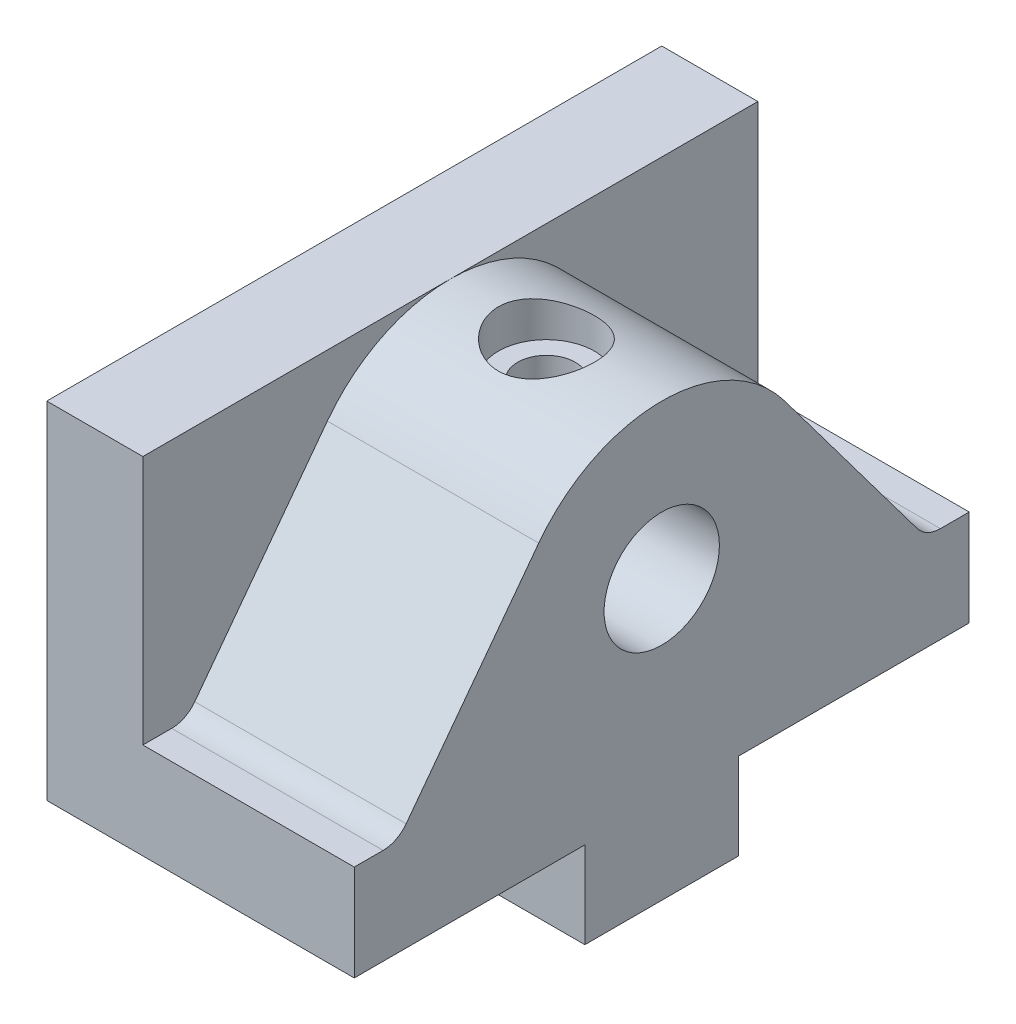
SolidWorks part; units mm, degrees
material "Gray Cast Iron"
ref_plane "Front Plane" through (0, 0, 0) normal (0, 0, 1) x (1, 0, 0)
ref_plane "Top Plane" through (0, 0, 0) normal (0, 1, 0) x (1, 0, 0)
ref_plane "Right Plane" through (0, 0, 0) normal (1, 0, 0) x (0, 0, -1)
sketch "Sketch1" plane through (0, 0, 0) normal (1, 0, 0) x (0, 0, -1)
  line L0 (8, -18) -> (32, -18)
  line L1 (-32, 18) -> (32, 18)
  line L2 (-32, 18) -> (-32, -18)
  line L3 (-32, -18) -> (-8, -18)
  line L4 (32, 18) -> (32, -18)
  line L5 (0, -18) -> (0, 18) construction
  line L6 (-32, 0) -> (32, 0) construction
  line L7 (-8, -27) -> (8, -27)
  line L8 (-8, -27) -> (-8, -18)
  line L10 (8, -27) -> (8, -18)
  line L11 (0, -18) -> (0, -27) construction
  line L12 (-8, -22.5) -> (8, -22.5) construction
  point P0 (0, 0)
  point P4 (0, -22.5)
  dimension "D1" = 36
  dimension "D2" = 64
  dimension "D3" = 16
  dimension "D4" = 9
extrude "Boss-Extrude1" add sketch "Sketch1" against normal blind 32
sketch "Sketch3" plane through (0, 0, 0) normal (1, 0, 0) x (0, 0, -1)
  line L0 (0, 32.7386) -> (0, -32.7386) construction
  line L6 (0, -18) -> (0, 18) construction
  line L7 (-32, 0) -> (32, 0) construction
  line L9 (32, 18) -> (-32, 18) construction
  line L10 (-27.5, -8) -> (-12.8, 11.6)
  line L11 (-32, -8) -> (-27.5, -8)
  line L12 (-32, -8) -> (-32, -18)
  line L13 (-32, -18) -> (-8, -18)
  line L14 (32, -8) -> (32, -18)
  line L15 (0, -18) -> (0, -8) construction
  line L16 (-32, -13) -> (32, -13) construction
  line L17 (27.5, -8) -> (12.8, 11.6)
  line L18 (32, -18) -> (32, 18) construction
  line L19 (27.5, -8) -> (32, -8)
  line L20 (8, -18) -> (32, -18)
  line L22 (-8, -18) -> (-8, -27)
  line L23 (-8, -27) -> (8, -27)
  line L24 (8, -18) -> (8, -27)
  arc A1 (12.8, 11.6) -> (-12.8, 11.6) centre (0, 2) ccw
  point P0 (0, 0)
  point P4 (0, 0)
  point P8 (0, -13)
  dimension "D1" = 16
  dimension "D3" = 10
  dimension "D4" = 4.5
  dimension "D5" = 4.5
  dimension "D6" = 55
extrude "Cut-Extrude1" cut sketch "Sketch3" against normal blind 22 flip side to cut contours L23 L24 L20 L14 L19 L17 A1 L10 L11 L12 L13 L22
sketch "Sketch6" plane through (0, 0, 0) normal (1, 0, 0) x (0, 0, -1)
  line L0 (0, 28.2069) -> (0, -28.2069) construction
  line L1 (0, 18) -> (32, 18) construction
  circle A0 centre (0, 2) radius 6
  point P6 (0, 0)
  dimension "D1" = 12
  dimension "D2" = 16
extrude "Cut-Extrude2" cut sketch "Sketch6" against normal blind 24
ref_plane "Plane1" through (0, 18, 0) normal (0, 1, 0) x (1, 0, 0)
sketch "Sketch7" plane through (0, 18, 0) normal (0, 1, 0) x (1, 0, 0)
  line L0 (-32, 32) -> (-32, -32) construction
  line L1 (-22, 32) -> (0, 32) construction
  circle A0 centre (-12, 0) radius 3
  point P4 (-32, 0)
  dimension "D1" = 6
  dimension "D2" = 20
  dimension "D3" = 32
extrude "Cut-Extrude3" cut sketch "Sketch7" against normal up to next
sketch "Sketch8" plane through (0, 18, 0) normal (0, 1, 0) x (1, 0, 0)
  circle A0 centre (-12, 0) radius 5
  dimension "D1" = 10
extrude "Cut-Extrude4" cut sketch "Sketch8" against normal blind 4
sketch "Sketch9" plane through (0, -27, 0) normal (0, -1, 0) x (1, 0, 0)
  line L0 (0, 8) -> (0, -8) construction
  line L5 (-32, 8) -> (0, 8) construction
  circle A0 centre (-8, 0) radius 3
  circle A1 centre (-24, 0) radius 3
  dimension "D1" = 6
  dimension "D3" = 6
  dimension "D2" = 8
  dimension "D4" = 16
  dimension "D5" = 8
hole_wizard "M6x1.0 Tapped Hole2" positions "Sketch12" profile "Sketch13" tap size "M6x1.0" standard "ANSI Metric"
sketch "Sketch12" plane through (0, -27, 0) normal (0, -1, 0) x (-1, 0, 0)
  point P0 (8, 0)
  point P3 (24, 0)
sketch "Sketch13" plane through (-8, -27, 0) normal (1, 0, 0) x (0, 0, -1)
  line L0 (0, 0) -> (0, 17.5022)
  line L1 (0, 17.5022) -> (2.5, 16)
  line L2 (2.5, 16) -> (2.5, 0.4405)
  line L3 (2.5, 0.4405) -> (3.025, 0)
  line L5 (3.025, 0) -> (0, 0)
  line L6 (-2.5, 0.4405) -> (-3.025, 0) construction
  line L10 (0, 17.5022) -> (-2.5, 16) construction
  line L11 (0, -6.35) -> (0, 107.95) construction
  dimension "Tap Drill Dia." = 5
  dimension "Tap Drill Depth" = 16
  dimension "Near C'Sink Dia." = 6.05
  dimension "Near C'Sink Angle" = 100
  dimension "Drill Angle" = 118
cosmetic thread "Hole Thread3" parameters "D1"=12, "D2"=6
cosmetic thread "Hole Thread4" parameters "D1"=12, "D2"=6
fillet "Fillet1" radius 3 2 edges at (-11, -8, -27.5) (-11, -8, 27.5)
